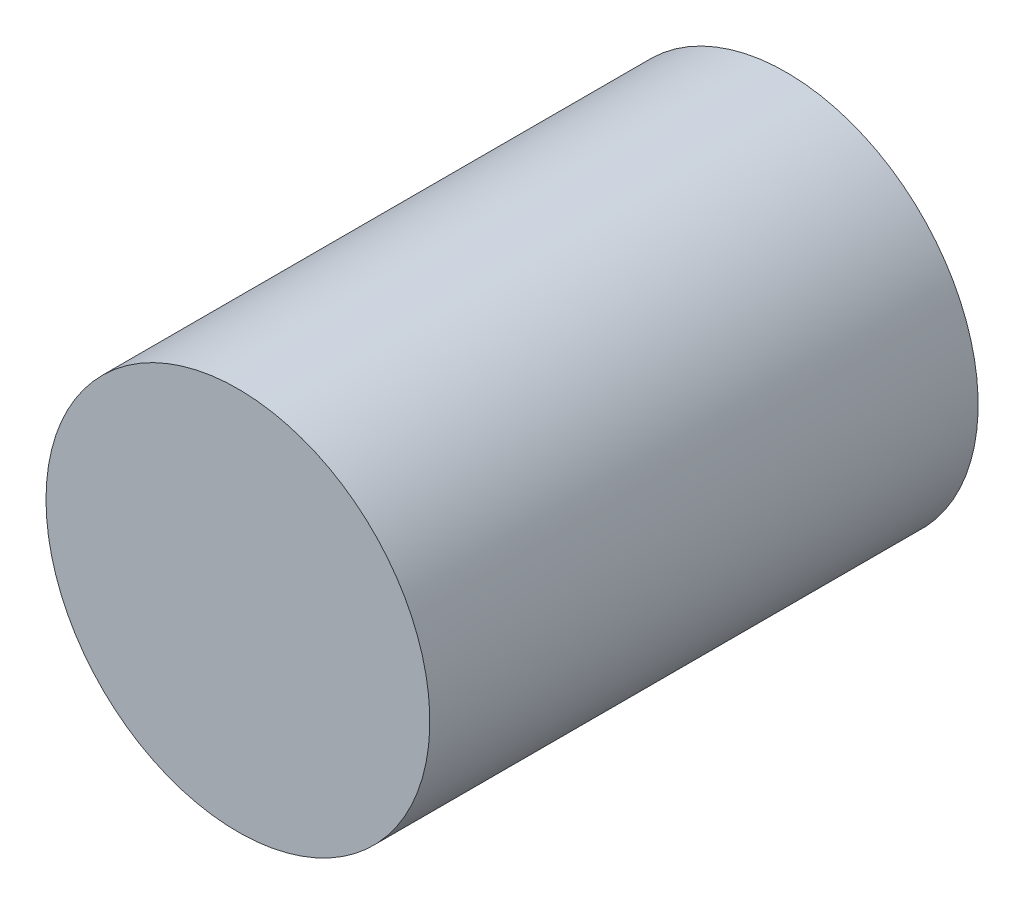
SolidWorks part; units mm, degrees
ref_plane "Front Plane" through (0, 0, 0) normal (0, 0, 1) x (1, 0, 0)
ref_plane "Top Plane" through (0, 0, 0) normal (0, 1, 0) x (1, 0, 0)
ref_plane "Right Plane" through (0, 0, 0) normal (1, 0, 0) x (0, 0, -1)
sketch "Sketch1" plane through (0, 0, 0) normal (0, 0, 1) x (1, 0, 0)
  circle A0 centre (0, 0) radius 4.445
  dimension "D1" = 8.89
extrude "Boss-Extrude1" add sketch "Sketch1" along normal blind 12.7
